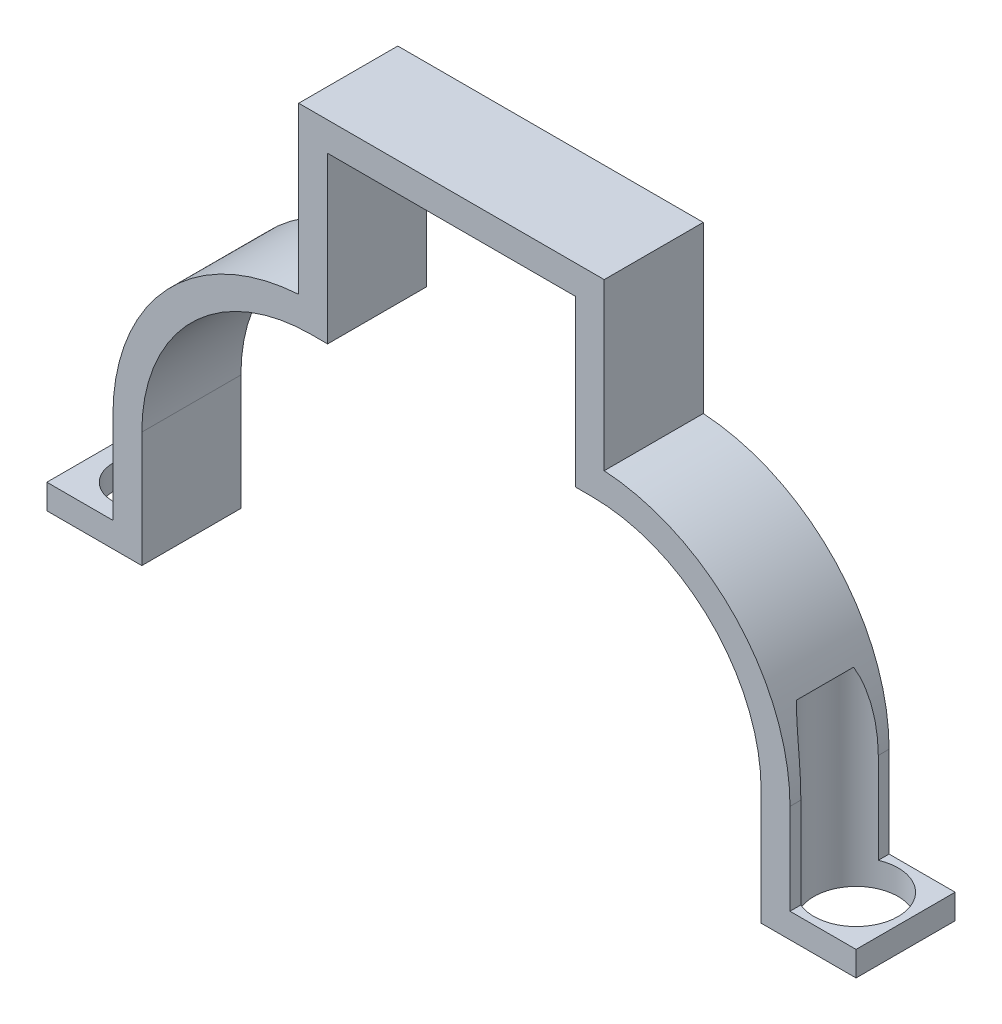
SolidWorks part; units mm, degrees
ref_plane "정면도" through (0, 0, 0) normal (0, 0, 1) x (1, 0, 0)
ref_plane "평면도" through (0, 0, 0) normal (0, 1, 0) x (1, 0, 0)
ref_plane "우측면도" through (0, 0, 0) normal (1, 0, 0) x (0, 0, -1)
sketch "스케치1" plane through (0, 0, 0) normal (0, 0, 1) x (1, 0, 0)
  line L0 (31.75, 18.5) -> (33, 18.5)
  line L1 (17.25, 28.5) -> (31.75, 28.5)
  line L2 (17.25, 28.5) -> (17.25, 18.5)
  line L3 (49, 3) -> (45, 3)
  line L4 (49, 1.5) -> (49, 3)
  line L5 (45, 3) -> (45, 8.5)
  line L6 (33.75, 30.5) -> (33.75, 20.4765)
  line L7 (49, 1.5) -> (43, 1.5)
  line L8 (43, 8.5) -> (43, 1.5)
  line L9 (6, 8.5) -> (6, 1.5)
  line L10 (0, 1.5) -> (6, 1.5)
  line L11 (31.75, 28.5) -> (31.75, 18.5)
  line L13 (15.25, 30.5) -> (33.75, 30.5)
  line L14 (15.25, 30.5) -> (15.25, 20.4765)
  line L15 (4, 3) -> (4, 8.5)
  line L16 (15.25, 30.5) -> (15.25, 18.5) construction
  line L17 (0, 1.5) -> (0, 3)
  line L18 (0, 3) -> (4, 3)
  line L19 (24.5, 30.5) -> (24.5, 0) construction
  line L20 (15.25, 30.5) -> (33.75, 30.5) construction
  line L21 (17.25, 28.5) -> (31.75, 28.5) construction
  line L22 (17.25, 18.5) -> (16, 18.5)
  line L23 (33.75, 30.5) -> (33.75, 18.5) construction
  line L24 (31.75, 28.5) -> (31.75, 18.5) construction
  arc A0 (33.75, 20.4765) -> (45, 8.5) centre (33, 8.5) cw
  arc A1 (16, 18.5) -> (6, 8.5) centre (16, 8.5) ccw
  arc A2 (15.25, 20.4765) -> (4, 8.5) centre (16, 8.5) ccw
  arc A3 (33, 18.5) -> (43, 8.5) centre (33, 8.5) cw
  point P10 (24.5, 28.5)
  dimension "D2" = 2
  dimension "D3" = 2
  dimension "D4" = 1.5
extrude "보스-돌출1" add sketch "스케치1" along normal blind 6
sketch "스케치2" plane through (0, 3, 0) normal (0, 1, 0) x (1, 0, 0)
  line L0 (43, -6) -> (43, 0) construction
  line L1 (43, -6) -> (43, 0) construction
  line L3 (43, -6) -> (49, 0) construction
  line L4 (49, -6) -> (43, 0) construction
  line L5 (6, -6) -> (6, 0) construction
  line L6 (6, -6) -> (6, 0) construction
  line L7 (6, 0) -> (0, -6) construction
  line L8 (6, -6) -> (0, 0) construction
  circle A0 centre (46, -3) radius 2.55
  circle A1 centre (3, -3) radius 2
  line M4 (45, 0) -> (45, -6)
  dimension "D1" = 5.1
  dimension "D2" = 4
extrude "컷-돌출1" cut sketch "스케치2" against normal blind 10 and the other way blind 10 contours A0 M4 | A0 M4 | A1
sketch "스케치3" plane through (0, 0, 6) normal (0, 0, 1) x (1, 0, 0)
  line L0 (5.75, 1.5) -> (5.75, 8.5)
  line L1 (16, 18.75) -> (17, 18.75)
  line L2 (17, 18.75) -> (17, 28.75)
  line L3 (17, 28.75) -> (32, 28.75)
  line L4 (32, 28.75) -> (32, 18.75)
  line L5 (32, 18.75) -> (33, 18.75)
  line L6 (43.25, 8.5) -> (43.25, 1.5)
  line L7 (43.25, 1.5) -> (43, 1.5)
  line L8 (5.75, 1.5) -> (6, 1.5)
  line L18 (17.25, 18.5) -> (17.25, 28.5)
  line L19 (17.25, 28.5) -> (31.75, 28.5)
  line L20 (31.75, 28.5) -> (31.75, 18.5)
  line L21 (31.75, 18.5) -> (33, 18.5)
  line L22 (43, 8.5) -> (43, 1.5)
  line L23 (43, 1.5) -> (49, 1.5)
  line L24 (49, 1.5) -> (49, 3)
  line L25 (49, 3) -> (45, 3)
  line L26 (45, 3) -> (45, 8.5)
  line L27 (33.75, 20.4765) -> (33.75, 30.5)
  line L28 (33.75, 30.5) -> (15.25, 30.5)
  line L29 (15.25, 30.5) -> (15.25, 20.4765)
  line L30 (4, 8.5) -> (4, 3)
  line L31 (4, 3) -> (0, 3)
  line L32 (0, 3) -> (0, 1.5)
  line L33 (0, 1.5) -> (6, 1.5)
  line L34 (6, 1.5) -> (6, 8.5)
  line L35 (16, 18.5) -> (17.25, 18.5)
  line L36 (17.25, 18.5) -> (17.25, 28.5)
  line L37 (17.25, 28.5) -> (31.75, 28.5)
  line L38 (31.75, 28.5) -> (31.75, 18.5)
  line L39 (31.75, 18.5) -> (33, 18.5)
  line L40 (43, 8.5) -> (43, 1.5)
  line L52 (6, 1.5) -> (6, 8.5)
  line L53 (16, 18.5) -> (17.25, 18.5)
  arc A0 (16, 18.75) -> (5.75, 8.5) centre (16, 8.5) ccw
  arc A1 (43.25, 8.5) -> (33, 18.75) centre (33, 8.5) ccw
  arc A4 (43, 8.5) -> (33, 18.5) centre (33, 8.5) ccw
  arc A5 (45, 8.5) -> (33.75, 20.4765) centre (33, 8.5) ccw
  arc A6 (15.25, 20.4765) -> (4, 8.5) centre (16, 8.5) ccw
  arc A7 (16, 18.5) -> (6, 8.5) centre (16, 8.5) ccw
  arc A8 (43, 8.5) -> (33, 18.5) centre (33, 8.5) ccw
  arc A11 (16, 18.5) -> (6, 8.5) centre (16, 8.5) ccw
  dimension "D1" = 0
  dimension "D2" = 0.25
extrude "컷-돌출2" cut sketch "스케치3" against normal blind 10
